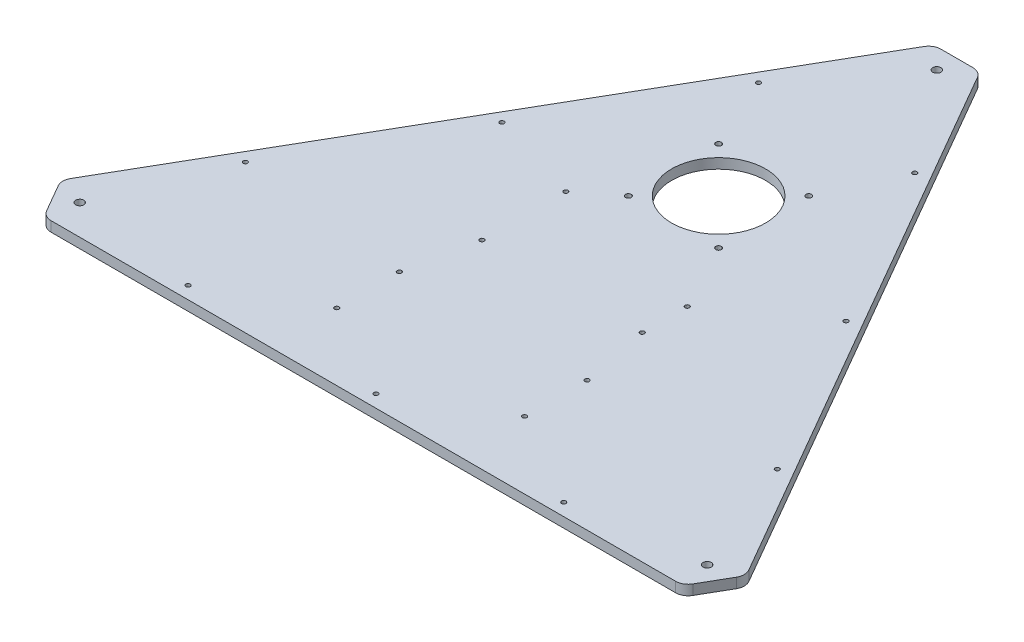
SolidWorks part; units mm, degrees
material "Керамика фарфор"
ref_plane "Спереди" through (0, 0, 0) normal (0, 0, 1) x (1, 0, 0)
ref_plane "Сверху" through (0, 0, 0) normal (0, 1, 0) x (1, 0, 0)
ref_plane "Справа" through (0, 0, 0) normal (1, 0, 0) x (0, 0, -1)
sketch "Эскиз1" plane through (0, 0, 0) normal (0, 1, 0) x (1, 0, 0)
  line L17 (273.664, -136.638) -> (18.5, 305.319)
  line L18 (18.5, 305.319) -> (-18.5, 305.319)
  line L19 (-18.5, 305.319) -> (-273.664, -136.638)
  line L31 (-273.664, -136.638) -> (-255.164, -168.681)
  line L32 (-255.164, -168.681) -> (255.164, -168.681)
  line L33 (255.164, -168.681) -> (273.664, -136.638)
  line L34 (-264.414, -152.6595) -> (0, 0) construction
  line L35 (0, 0) -> (146.082, 84.3405) construction
  line L36 (264.414, -152.6595) -> (0, 0) construction
  line L37 (0, 0) -> (-146.082, 84.3405) construction
  line L38 (0, 305.319) -> (0, 0) construction
  line L39 (0, 0) -> (0, -168.681) construction
  line L41 (-36, 151) -> (36, 151) construction
  line L42 (-36, 151) -> (-36, 79) construction
  line L43 (-36, 79) -> (36, 79) construction
  line L44 (36, 151) -> (36, 79) construction
  line L45 (-36, 151) -> (36, 79) construction
  line L46 (-36, 79) -> (36, 151) construction
  line L47 (75, -115) -> (0, -115) construction
  line L48 (0, -115) -> (-75, -115) construction
  line L49 (64, -10) -> (0, -10) construction
  line L50 (0, -10) -> (-64, -10) construction
  circle A0 centre (-250.5576, -144.6595) radius 3.25
  circle A1 centre (250.5576, -144.6595) radius 3.25
  circle A2 centre (0, 289.319) radius 3.25
  circle A3 centre (0, 115) radius 37.5
  circle A4 centre (36, 151) radius 2.25
  circle A5 centre (-36, 151) radius 2.25
  circle A6 centre (-36, 79) radius 2.25
  circle A7 centre (36, 79) radius 2.25
  circle A8 centre (-64, 57) radius 1.75
  circle A9 centre (-64, -10) radius 1.75
  circle A10 centre (64, -10) radius 1.75
  circle A11 centre (64, 26) radius 1.75
  circle A12 centre (75, -65) radius 1.75
  circle A13 centre (75, -115) radius 1.75
  circle A14 centre (-75, -115) radius 1.75
  circle A15 centre (-75, -65) radius 1.75
  point P3 (0, -168.681)
  point P11 (0, 305.319)
  point P32 (75, -115)
  point P33 (-75, -115)
  point P34 (-75, -65)
  point P35 (75, -65)
  point P36 (64, -10)
  point P37 (-64, -10)
  point P38 (-64, 57)
  point P39 (64, 26)
  dimension "D13" = 150
  dimension "D4" = 6.5
  dimension "D8" = 75
  dimension "D12" = 4.5
  dimension "D20" = 3.5
  dimension "D1" = 60
  dimension "D2" = 474
  dimension "D3" = 37
  dimension "D5" = 16
  dimension "D6" = 16
  dimension "D7" = 16
  dimension "D9" = 115
  dimension "D10" = 72
  dimension "D11" = 72
  dimension "D14" = 50
  dimension "D15" = 128
  dimension "D16" = 36
  dimension "D17" = 67
  dimension "D18" = 115
  dimension "D19" = 10
extrude "База" add sketch "Эскиз1" along normal mid plane 8
fillet "Скругление1" radius 10 6 edges at (273.664, 0, 136.638) (255.164, 0, 168.681) (-255.164, 0, 168.681) (-273.664, 0, 136.638) (18.5, 0, -305.319) (-18.5, 0, -305.319)
hole_wizard "К Профилю 3,5мм" positions "Эскиз4" profile "Эскиз5" hole size "Ø3.5" standard "DIN" end condition through all
sketch "Эскиз4" plane through (0, 4, 0) normal (0, 1, 0) x (1, 0, 0)
  line L0 (-212.4218, -50.5633) -> (-137.4218, 79.3405) construction
  line L1 (-137.4218, 79.3405) -> (-62.4218, 209.2443) construction
  line L4 (62.4218, 209.2443) -> (137.4218, 79.3405) construction
  line L5 (137.4218, 79.3405) -> (212.4218, -50.5633) construction
  line L8 (150, -158.681) -> (0, -158.681) construction
  line L9 (0, -158.681) -> (-150, -158.681) construction
  line L12 (0, -158.681) -> (137.4218, 79.3405) construction
  line L13 (137.4218, 79.3405) -> (-137.4218, 79.3405) construction
  line L14 (-137.4218, 79.3405) -> (0, -158.681) construction
  line L17 (-249.3905, -168.681) -> (249.3905, -168.681) construction
  line L18 (-21.3868, 300.319) -> (-270.7773, -131.638) construction
  point P0 (-137.4218, 79.3405)
  point P2 (-62.4218, 209.2443)
  point P4 (62.4218, 209.2443)
  point P6 (137.4218, 79.3405)
  point P8 (212.4218, -50.5633)
  point P10 (150, -158.681)
  point P12 (0, -158.681)
  point P14 (-150, -158.681)
  point P16 (-212.4218, -50.5633)
  dimension "D1" = 10
  dimension "D2" = 10
  dimension "D3" = 300
  dimension "D4" = 60
  dimension "D5" = 60
sketch "Эскиз5" plane through (-137.4218, 4, -79.3405) normal (1, 0, 0) x (0, 0, 1)
  line L0 (0, 0) -> (0, 8)
  line L1 (0, 8) -> (1.75, 8)
  line L2 (1.75, 8) -> (1.75, 0)
  line L5 (1.75, 0) -> (0, 0)
  line L11 (0, -6.35) -> (0, 107.95) construction
  dimension "Диаметр сквозного отверстия" = 3.5
  dimension "Глубина сквозного отверстия" = 8
